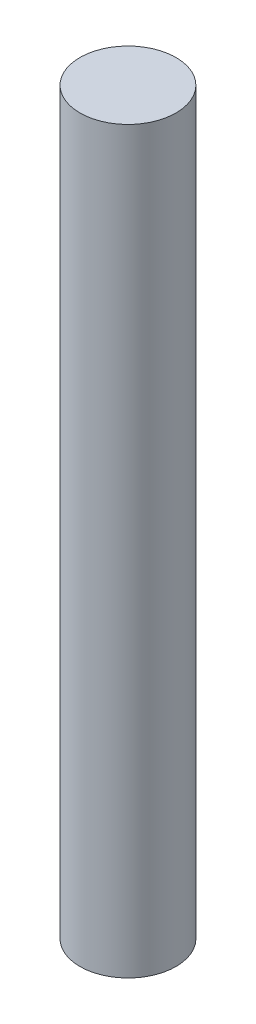
SolidWorks part; units mm, degrees
material "PTFE (general)"
ref_plane "Front Plane" through (0, 0, 0) normal (0, 0, 1) x (1, 0, 0)
ref_plane "Top Plane" through (0, 0, 0) normal (0, 1, 0) x (1, 0, 0)
ref_plane "Right Plane" through (0, 0, 0) normal (1, 0, 0) x (0, 0, -1)
sketch "Sketch1" plane through (0, 0, 0) normal (0, 1, 0) x (1, 0, 0)
  circle A0 centre (0, 0) radius 3.25
  dimension "D1" = 6.5
extrude "Boss-Extrude1" add sketch "Sketch1" along normal blind 50
